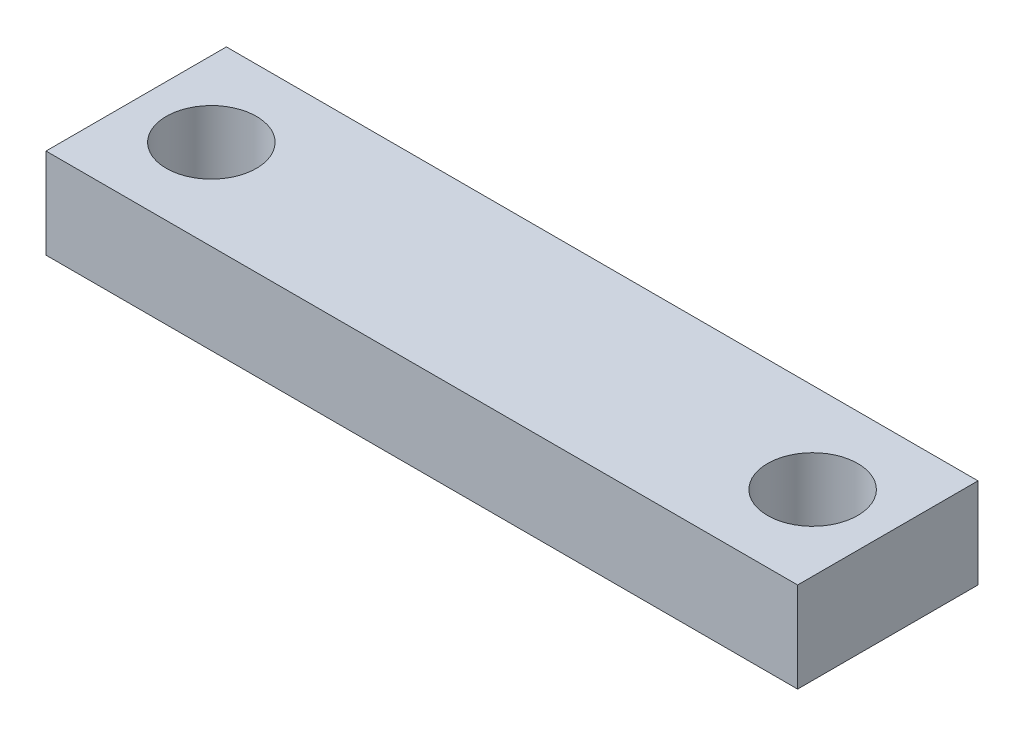
SolidWorks part; units mm, degrees
ref_plane "Front Plane" through (0, 0, 0) normal (0, 0, 1) x (1, 0, 0)
ref_plane "Top Plane" through (0, 0, 0) normal (0, 1, 0) x (1, 0, 0)
ref_plane "Right Plane" through (0, 0, 0) normal (1, 0, 0) x (0, 0, -1)
sketch "Sketch1" plane through (0, 0, 0) normal (0, 1, 0) x (1, 0, 0)
  line L1 (0, 0) -> (25, 0)
  line L2 (0, 0) -> (0, -6)
  line L3 (0, -6) -> (25, -6)
  line L4 (25, 0) -> (25, -6)
  dimension "D1" = 25
  dimension "D2" = 6
extrude "Boss-Extrude1" add sketch "Sketch1" along normal blind 3
sketch "Sketch2" plane through (0, 3, 0) normal (0, 1, 0) x (1, 0, 0)
  line L0 (25, 0) -> (0, 0) construction
  line L1 (25, -6) -> (25, 0) construction
  line L2 (0, 0) -> (0, -6) construction
  circle A0 centre (2.5, -3) radius 1.5
  circle A1 centre (22.5, -3) radius 1.5
  point P0 (22.5, -3)
  point P6 (2.5, -3)
  dimension "D4" = 3
  dimension "D5" = 3
  dimension "D1" = 3
  dimension "D2" = 2.5
  dimension "D3" = 2.5
extrude "Cut-Extrude1" cut sketch "Sketch2" against normal blind 3
